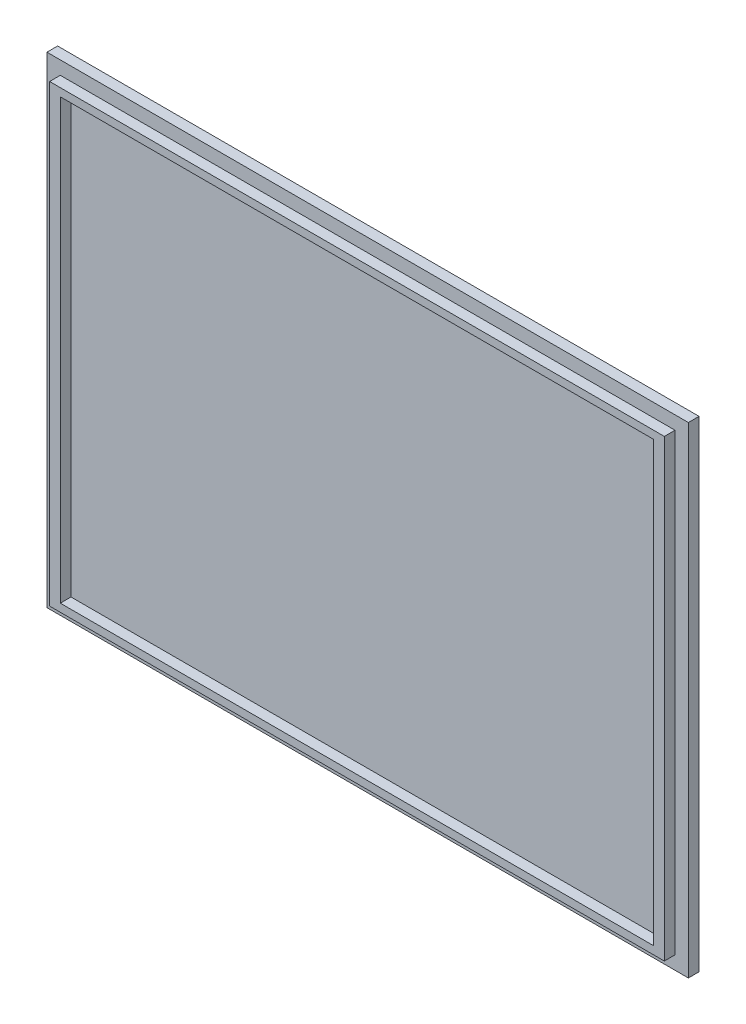
SolidWorks part; units mm, degrees
ref_plane "Plan de face" through (0, 0, 0) normal (0, 0, 1) x (1, 0, 0)
ref_plane "Plan de dessus" through (0, 0, 0) normal (0, 1, 0) x (1, 0, 0)
ref_plane "Plan de droite" through (0, 0, 0) normal (1, 0, 0) x (0, 0, -1)
sketch "Esquisse1" plane through (0, 0, 0) normal (0, 0, 1) x (1, 0, 0)
  line L1 (60, -45) -> (-60, -45)
  line L2 (60, -45) -> (60, 45)
  line L3 (60, 45) -> (-60, 45)
  line L4 (-60, -45) -> (-60, 45)
  line L5 (60, -45) -> (-60, 45) construction
  line L6 (60, 45) -> (-60, -45) construction
  point P0 (0, 0)
  dimension "D1" = 120
  dimension "D2" = 90
extrude "Boss.-Extru.1" add sketch "Esquisse1" along normal blind 2
sketch "Esquisse2" plane through (0, 0, 2) normal (0, 0, 1) x (1, 0, 0)
  line L1 (57.5, -42.5) -> (-57.5, -42.5)
  line L2 (57.5, -42.5) -> (57.5, 42.5)
  line L3 (57.5, 42.5) -> (-57.5, 42.5)
  line L4 (-57.5, -42.5) -> (-57.5, 42.5)
  line L5 (57.5, -42.5) -> (-57.5, 42.5) construction
  line L6 (57.5, 42.5) -> (-57.5, -42.5) construction
  line L7 (55.5, -41.0217) -> (-55.5, -41.0217)
  line L8 (55.5, -41.0217) -> (55.5, 41.0217)
  line L9 (55.5, 41.0217) -> (-55.5, 41.0217)
  line L10 (-55.5, -41.0217) -> (-55.5, 41.0217)
  line L11 (55.5, -41.0217) -> (-55.5, 41.0217) construction
  line L12 (55.5, 41.0217) -> (-55.5, -41.0217) construction
  point P0 (0, 0)
  point P6 (0, 0)
  dimension "D1" = 115
  dimension "D2" = 85
  dimension "D3" = 2
extrude "Boss.-Extru.2" add sketch "Esquisse2" along normal blind 2
